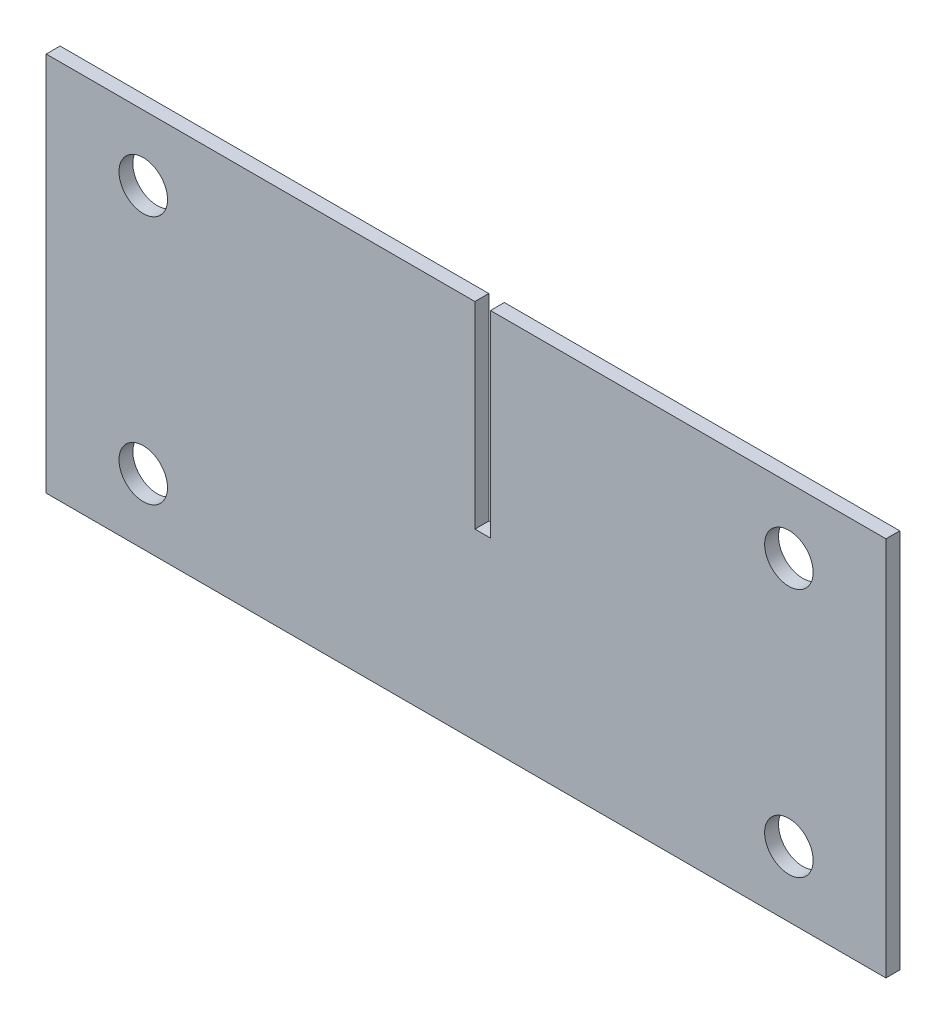
SolidWorks part; units mm, degrees
ref_plane "Front Plane" through (0, 0, 0) normal (0, 0, 1) x (1, 0, 0)
ref_plane "Top Plane" through (0, 0, 0) normal (0, 1, 0) x (1, 0, 0)
ref_plane "Right Plane" through (0, 0, 0) normal (1, 0, 0) x (0, 0, -1)
sketch "Sketch1" plane through (0, 0, 0) normal (0, 0, 1) x (1, 0, 0)
  line L0 (1527.3098, 238.9156) -> (1527.3098, 39.2716) construction
  line L1 (1438.4098, 226.2156) -> (1823.0928, 226.2156)
  line L2 (1438.4098, 226.2156) -> (1438.4098, 51.9716)
  line L3 (1438.4098, 51.9716) -> (1823.0928, 51.9716)
  line L4 (1823.0928, 226.2156) -> (1823.0928, 51.9716)
  line L5 (1734.1928, 39.2716) -> (1734.1928, 238.9156) construction
  line L6 (4782.1928, 238.9156) -> (1734.1928, 238.9156) construction
  line L7 (4782.1928, 39.2716) -> (1734.1928, 39.2716) construction
  dimension "D1" = 88.9
  dimension "D2" = 88.9
  dimension "D3" = 12.7
  dimension "D4" = 12.7
extrude "Boss-Extrude1" add sketch "Sketch1" along normal blind 6.35
sketch "Sketch2" plane through (0, 0, 6.35) normal (0, 0, 1) x (1, 0, 0)
  line L0 (1823.0928, 139.0936) -> (1734.1928, 139.0936) construction
  line L1 (1823.0928, 51.9716) -> (1823.0928, 226.2156) construction
  line L2 (1734.1928, 39.2716) -> (1734.1928, 238.9156) construction
  line L3 (1778.6428, 196.2436) -> (1778.6428, 81.9436) construction
  line L7 (1438.4098, 139.0936) -> (1527.3098, 139.0936) construction
  line L8 (1438.4098, 226.2156) -> (1438.4098, 51.9716) construction
  line L9 (1527.3098, 238.9156) -> (1527.3098, 39.2716) construction
  line L10 (1482.8598, 196.2436) -> (1482.8598, 81.9436) construction
  circle A0 centre (1778.6428, 196.2436) radius 11.1125
  circle A1 centre (1778.6428, 81.9436) radius 11.1125
  circle A2 centre (1482.8598, 196.2436) radius 11.1125
  circle A3 centre (1482.8598, 81.9436) radius 11.1125
  point P8 (1778.6428, 139.0936)
  point P19 (1482.8598, 139.0936)
  dimension "D2" = 22.225
  dimension "D1" = 114.3
extrude "Cut-Extrude1" cut sketch "Sketch2" against normal up to next
sketch "Sketch3" plane through (0, 0, 6.35) normal (0, 0, 1) x (1, 0, 0)
  line L0 (1823.0928, 226.2156) -> (1438.4098, 226.2156) construction
  line L1 (1641.9431, 226.2156) -> (1634.7994, 226.2156)
  line L2 (1641.9431, 226.2156) -> (1641.9431, 135.9186)
  line L3 (1641.9431, 135.9186) -> (1634.7994, 135.9186)
  line L4 (1634.7994, 226.2156) -> (1634.7994, 135.9186)
  line L5 (1638.3713, 226.2156) -> (1638.3713, 51.9716) construction
  line L6 (1641.5463, 51.9716) -> (1635.1963, 51.9716) construction
  line L7 (1641.5463, 226.2156) -> (1635.1963, 226.2156) construction
  line L8 (1635.1963, 226.2156) -> (1635.1963, 51.9716) construction
  point P12 (1638.3713, 135.9186)
  point P15 (1638.3713, 139.0936)
  dimension "D1" = 0.3969
  dimension "D2" = 3.175
extrude "Cut-Extrude2" cut sketch "Sketch3" against normal up to next
